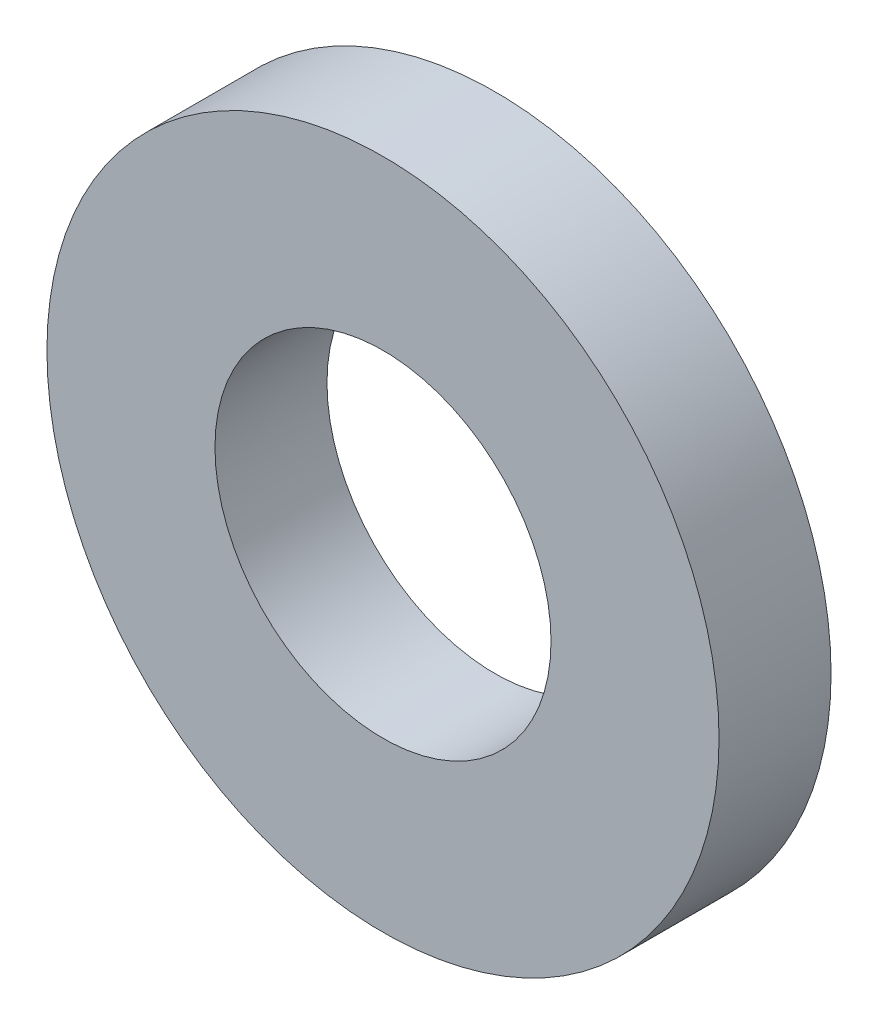
SolidWorks part; units mm, degrees
ref_plane "Front Plane" through (0, 0, 0) normal (0, 0, 1) x (1, 0, 0)
ref_plane "Top Plane" through (0, 0, 0) normal (0, 1, 0) x (1, 0, 0)
ref_plane "Right Plane" through (0, 0, 0) normal (1, 0, 0) x (0, 0, -1)
sketch "Sketch1" plane through (0, 0, 0) normal (0, 0, 1) x (1, 0, 0)
  circle A0 centre (0, 0) radius 3
  dimension "D1" = 6
extrude "Boss-Extrude1" add sketch "Sketch1" along normal blind 1
sketch "Sketch2" plane through (0, 0, 0) normal (0, 0, -1) x (-1, 0, 0)
  circle A0 centre (0, 0) radius 1.5
  dimension "D1" = 3
extrude "Cut-Extrude1" cut sketch "Sketch2" against normal blind 1
